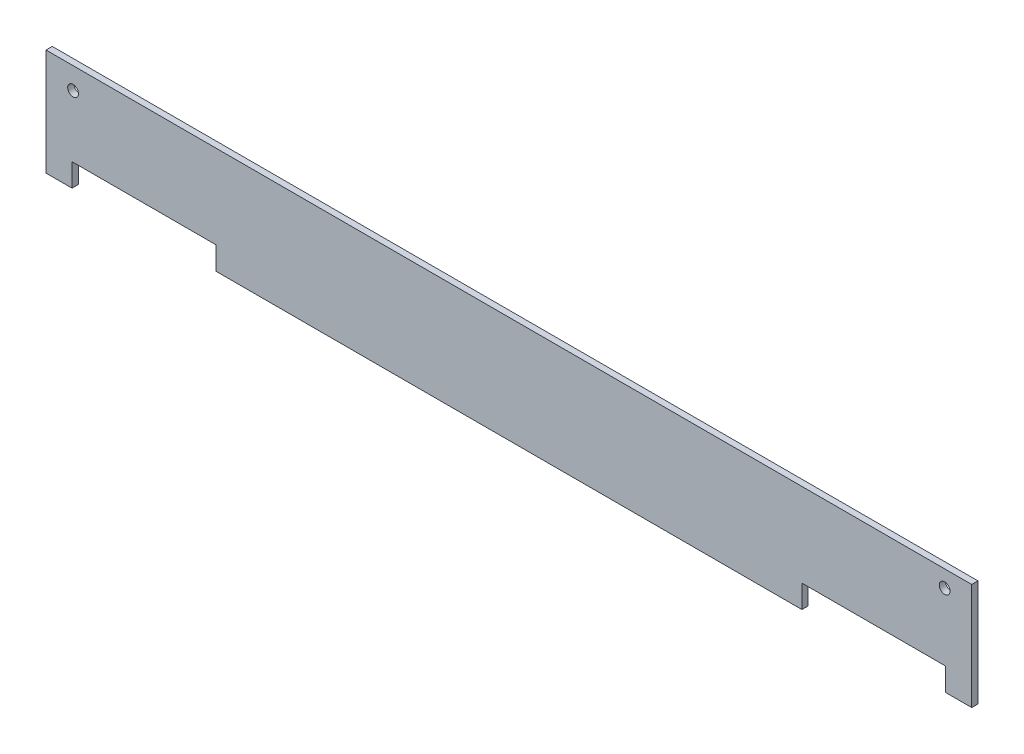
SolidWorks part; units mm, degrees
ref_plane "Plan de face" through (0, 0, 0) normal (0, 0, 1) x (1, 0, 0)
ref_plane "Plan de dessus" through (0, 0, 0) normal (0, 1, 0) x (1, 0, 0)
ref_plane "Plan de droite" through (0, 0, 0) normal (1, 0, 0) x (0, 0, -1)
sketch "Esquisse1" plane through (0, 0, 0) normal (0, 0, 1) x (1, 0, 0)
  line L1 (0, 0) -> (-444.3, 0)
  line L2 (0, 0) -> (0, 51.18)
  line L3 (0, 51.18) -> (-444.3, 51.18)
  line L4 (-444.3, 0) -> (-444.3, 51.18)
  dimension "D1" = 51.18
  dimension "D2" = 444.3
extrude "Boss.-Extru.1" add sketch "Esquisse1" along normal blind 3
sketch "Esquisse2" plane through (0, 0, 3) normal (0, 0, 1) x (1, 0, 0)
  circle A0 centre (-13, 43.1658) radius 2.6 construction
  circle A1 centre (-431.3, 40.7748) radius 2.6 construction
  circle A2 centre (-13, 43.1658) radius 2.6
  circle A3 centre (-431.3, 40.7748) radius 2.6
extrude "Enlèv. mat.-Extru.1" cut sketch "Esquisse2" against normal blind 20
sketch "Esquisse3" plane through (0, 0, 0) normal (0, -1, 0) x (1, 0, 0)
  line L0 (-444.3, 3) -> (0, 3) construction
  line L1 (-431.8, 3) -> (-362.8, 3)
  line L2 (-431.8, 3) -> (-431.8, 0)
  line L3 (-431.8, 0) -> (-362.8, 0)
  line L4 (-362.8, 3) -> (-362.8, 0)
  line L5 (-444.3, 0) -> (0, 0) construction
  line L6 (-444.3, 3) -> (-444.3, 0) construction
  line L7 (0, 3) -> (0, 0) construction
  line L8 (-12.5, 3) -> (-81.5, 3)
  line L9 (-12.5, 3) -> (-12.5, 0)
  line L10 (-12.5, 0) -> (-81.5, 0)
  line L11 (-81.5, 3) -> (-81.5, 0)
  point P10 (-431.8, 1.5)
  dimension "D1" = 12.5
  dimension "D2" = 69
  dimension "D3" = 12.5
  dimension "D4" = 69
extrude "Enlèv. mat.-Extru.2" cut sketch "Esquisse3" against normal blind 11
